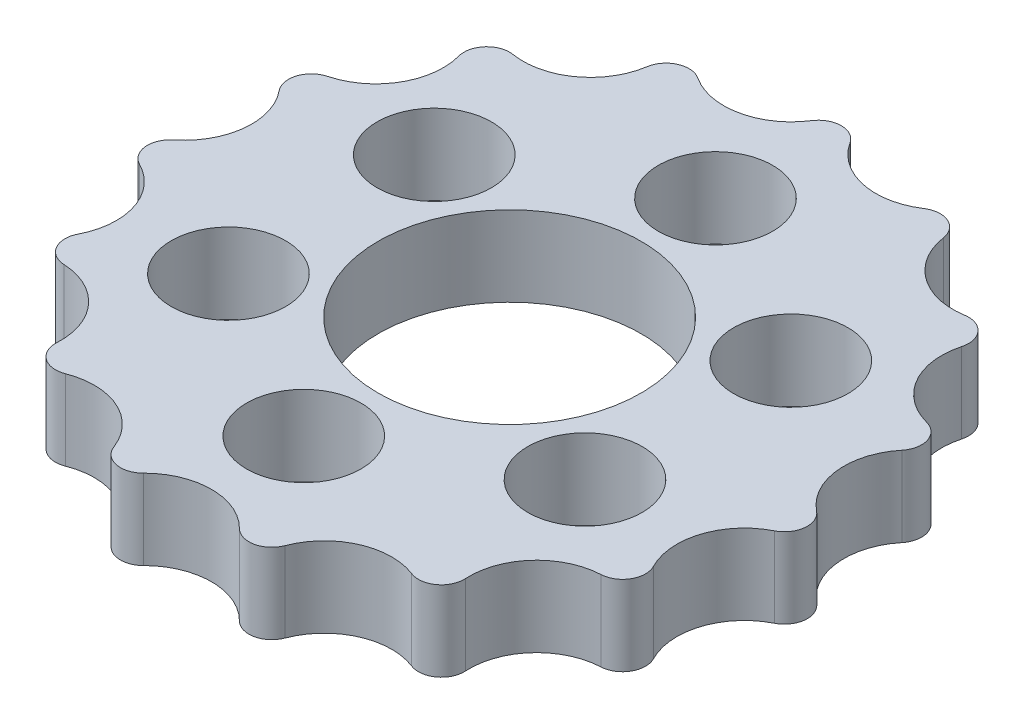
SolidWorks part; units mm, degrees
ref_plane "Front Plane" through (0, 0, 0) normal (0, 0, 1) x (1, 0, 0)
ref_plane "Top Plane" through (0, 0, 0) normal (0, 1, 0) x (1, 0, 0)
ref_plane "Right Plane" through (0, 0, 0) normal (1, 0, 0) x (0, 0, -1)
sketch "Sketch1" plane through (0, 0, 0) normal (0, 1, 0) x (1, 0, 0)
  arc A0 (1.6823, 28.0816) -> (-1.6823, 28.0816) centre (0, 27) ccw
  arc A1 (12.9587, 24.9695) -> (9.8849, 26.3381) centre (10.9819, 24.6657) ccw
  arc A2 (21.9944, 17.54) -> (19.743, 20.0404) centre (20.0649, 18.0665) ccw
  arc A3 (27.227, 7.0777) -> (26.1873, 10.2777) centre (25.6785, 8.3435) ccw
  arc A4 (27.7519, -4.6084) -> (28.1036, -1.2622) centre (26.8521, -2.8223) ccw
  arc A5 (23.4782, -15.4977) -> (25.1605, -12.5839) centre (23.3827, -13.5) ccw
  arc A6 (15.1449, -23.7073) -> (17.867, -21.7296) centre (15.8702, -21.8435) ccw
  arc A7 (4.1929, -27.8177) -> (7.484, -27.1182) centre (5.6136, -26.41) ccw
  arc A8 (-7.484, -27.1182) -> (-4.1929, -27.8177) centre (-5.6136, -26.41) ccw
  arc A9 (-17.867, -21.7296) -> (-15.1449, -23.7073) centre (-15.8702, -21.8435) ccw
  arc A10 (-25.1605, -12.5839) -> (-23.4782, -15.4977) centre (-23.3827, -13.5) ccw
  arc A11 (-28.1036, -1.2622) -> (-27.7519, -4.6084) centre (-26.8521, -2.8223) ccw
  arc A12 (-26.1873, 10.2777) -> (-27.227, 7.0777) centre (-25.6785, 8.3435) ccw
  arc A13 (-19.743, 20.0404) -> (-21.9944, 17.54) centre (-20.0649, 18.0665) ccw
  arc A14 (-9.8849, 26.3381) -> (-12.9587, 24.9695) centre (-10.9819, 24.6657) ccw
  arc A16 (21.9944, 17.54) -> (26.1873, 10.2777) centre (27.6889, 15.9862) ccw
  arc A18 (27.227, 7.0777) -> (28.1036, -1.2622) centre (31.7972, 3.342) ccw
  arc A19 (27.7519, -4.6084) -> (25.1605, -12.5839) centre (30.4075, -9.88) ccw
  arc A20 (23.4782, -15.4977) -> (17.867, -21.7296) centre (23.7601, -21.3937) ccw
  arc A21 (15.1449, -23.7073) -> (7.484, -27.1182) centre (13.0043, -29.2082) ccw
  arc A22 (4.1929, -27.8177) -> (-4.1929, -27.8177) centre (0, -31.9724) ccw
  arc A23 (-7.484, -27.1182) -> (-15.1449, -23.7073) centre (-13.0043, -29.2082) ccw
  arc A24 (-17.867, -21.7296) -> (-23.4782, -15.4977) centre (-23.7601, -21.3937) ccw
  arc A25 (-25.1605, -12.5839) -> (-27.7519, -4.6084) centre (-30.4075, -9.88) ccw
  arc A26 (-28.1036, -1.2622) -> (-27.227, 7.0777) centre (-31.7972, 3.342) ccw
  arc A27 (-26.1873, 10.2777) -> (-21.9944, 17.54) centre (-27.6889, 15.9862) ccw
  arc A28 (-19.743, 20.0404) -> (-12.9587, 24.9695) centre (-18.7929, 25.8662) ccw
  arc A29 (-9.8849, 26.3381) -> (-1.6823, 28.0816) centre (-6.6474, 31.2737) ccw
  arc A30 (1.6823, 28.0816) -> (9.8849, 26.3381) centre (6.6474, 31.2737) ccw
  arc A31 (12.9587, 24.9695) -> (19.743, 20.0404) centre (18.7929, 25.8662) ccw
  point P4 (0, 29)
  point P35 (0, 0)
  point P82 (0, 0)
  dimension "D1" = 2
  dimension "D2" = 29
  dimension "D3" = 15
  dimension "D4" = 15
extrude "Boss-Extrude1" add sketch "Sketch1" along normal blind 7 contours A28 A14 A29 A0 A30 A1 A31 A2 A16 A3 A18 A4 A19 A5 A20 A6 A21 A7 A22 A8 A23 A9 A24 A10 A25 A11 A26 A12 A27 A13
sketch "Sketch2" plane through (0, 7, 0) normal (0, 1, 0) x (1, 0, 0)
  circle A0 centre (0, 0) radius 11.5
  circle A1 centre (0, 18) radius 5
  circle A2 centre (15.5885, 9) radius 5
  circle A3 centre (15.5885, -9) radius 5
  circle A4 centre (0, -18) radius 5
  circle A5 centre (-15.5885, -9) radius 5
  circle A6 centre (-15.5885, 9) radius 5
  point P18 (0, 0)
  dimension "D1" = 23
  dimension "D2" = 10
  dimension "D4" = 18
  dimension "D3" = 6
extrude "Cut-Extrude1" cut sketch "Sketch2" against normal through all contours A1 | A0 | A5 | A4 | A3 | A2 | A6
